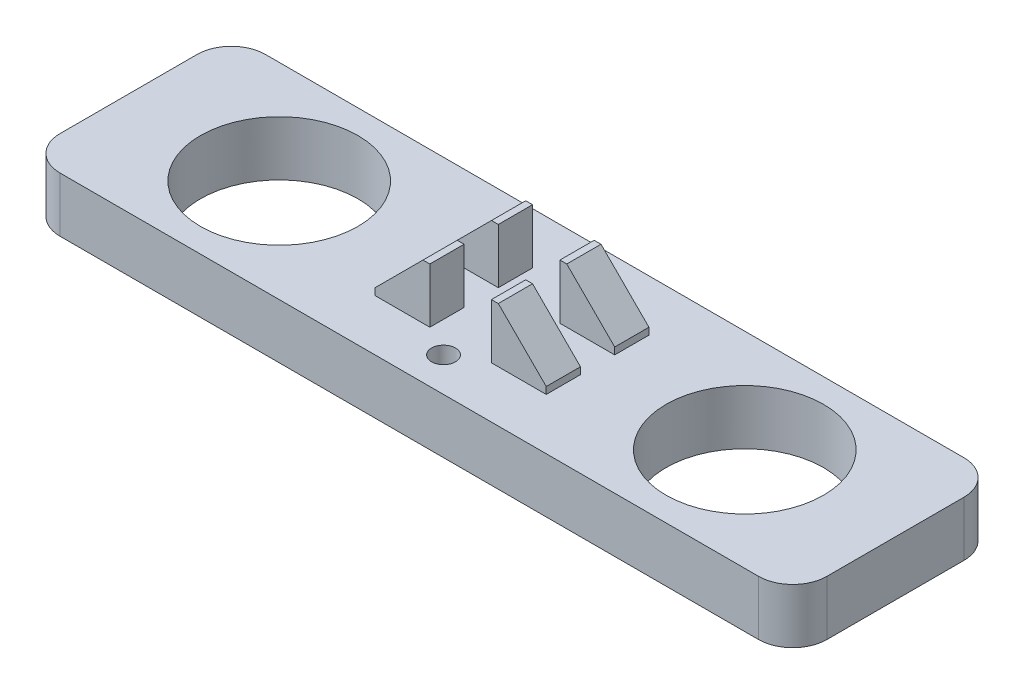
SolidWorks part; units mm, degrees
ref_plane "Front Plane" through (0, 0, 0) normal (0, 0, 1) x (1, 0, 0)
ref_plane "Top Plane" through (0, 0, 0) normal (0, 1, 0) x (1, 0, 0)
ref_plane "Right Plane" through (0, 0, 0) normal (1, 0, 0) x (0, 0, -1)
sketch "Sketch1" plane through (0, 0, 0) normal (0, 1, 0) x (1, 0, 0)
  line L1 (0, 0) -> (60, 0)
  line L2 (0, 0) -> (0, 30)
  line L3 (0, 30) -> (60, 30)
  line L4 (60, 0) -> (60, 30)
  circle A0 centre (22, 15) radius 11.5
  point P7 (0, 15)
  dimension "D3" = 23
  dimension "D4" = 22
  dimension "D1" = 60
  dimension "D2" = 30
extrude "Boss-Extrude1" add sketch "Sketch1" along normal blind 5
sketch "Sketch2" plane through (0, 5, 0) normal (0, 1, 0) x (1, 0, 0)
  line L0 (60, 0) -> (60, 30) construction
  line L1 (0, 0) -> (60, 0) construction
  line L2 (60, 30) -> (0, 30) construction
  circle A0 centre (56, 25) radius 1.75
  circle A1 centre (56, 5) radius 1.75
  dimension "D1" = 3.5
  dimension "D4" = 5
  dimension "D2" = 4
  dimension "D3" = 5
extrude "Cut-Extrude1" cut sketch "Sketch2" against normal through all
fillet "Fillet1" radius 5 2 edges at (0, 2.5, 0) (0, 2.5, -30)
sketch "Sketch6" plane through (0, 0, 0) normal (0, -1, 0) x (1, 0, 0)
  line L12 (60, 0) -> (5, 0)
  line L13 (0, -5) -> (0, -25)
  line L14 (5, -30) -> (60, -30)
  line L15 (60, -30) -> (60, 0)
  line L18 (60, 0) -> (5, 0)
  line L19 (0, -5) -> (0, -25)
  line L20 (5, -30) -> (60, -30)
  line L21 (60, -30) -> (60, 0)
  arc A8 (5, 0) -> (0, -5) centre (5, -5) ccw
  arc A9 (0, -25) -> (5, -30) centre (5, -25) ccw
  arc A12 (5, 0) -> (0, -5) centre (5, -5) ccw
  arc A13 (0, -25) -> (5, -30) centre (5, -25) ccw
  dimension "D1" = 0
extrude "Boss-Extrude4" add sketch "Sketch6" along normal blind 3
ref_plane "Plane1" through (56, 0, 0) normal (1, 0, 0) x (0, 0, -1)
mirror "Mirror1" about plane through (56, 0, 0) normal (1, 0, 0) of "Boss-Extrude4", "Fillet1", "Cut-Extrude1", "Boss-Extrude1"
sketch "Sketch7" plane through (0, 5, 0) normal (0, 1, 0) x (1, 0, 0)
  line L0 (0, 25) -> (0, 5) construction
  line L1 (43.5, 22.5) -> (51.5, 22.5)
  line L2 (43.5, 22.5) -> (43.5, 17.5)
  line L3 (43.5, 17.5) -> (51.5, 17.5)
  line L4 (51.5, 22.5) -> (51.5, 17.5)
  line L5 (60.5, 22.5) -> (68.5, 22.5)
  line L6 (60.5, 22.5) -> (60.5, 17.5)
  line L7 (60.5, 17.5) -> (68.5, 17.5)
  line L8 (68.5, 22.5) -> (68.5, 17.5)
  line L9 (5, 0) -> (107, 0) construction
  line L10 (107, 30) -> (5, 30) construction
  point P8 (0, 15)
  point P9 (51.5, 20)
  point P12 (56, 0)
  point P13 (43.5, 20)
  dimension "D1" = 9
  dimension "D2" = 5
  dimension "D3" = 8
  dimension "D4" = 4.5
  dimension "D5" = 7.5
extrude "Boss-Extrude5" add sketch "Sketch7" along normal blind 8
chamfer "Chamfer1" distance 7 angle 45 2 edges at (68.5, 13, -20) (43.5, 13, -20)
ref_plane "Plane2" through (0, 0, -15) normal (0, 0, -1) x (-1, 0, 0)
mirror "Mirror2" about plane through (0, 0, -15) normal (0, 0, -1) of "Chamfer1", "Boss-Extrude5"
